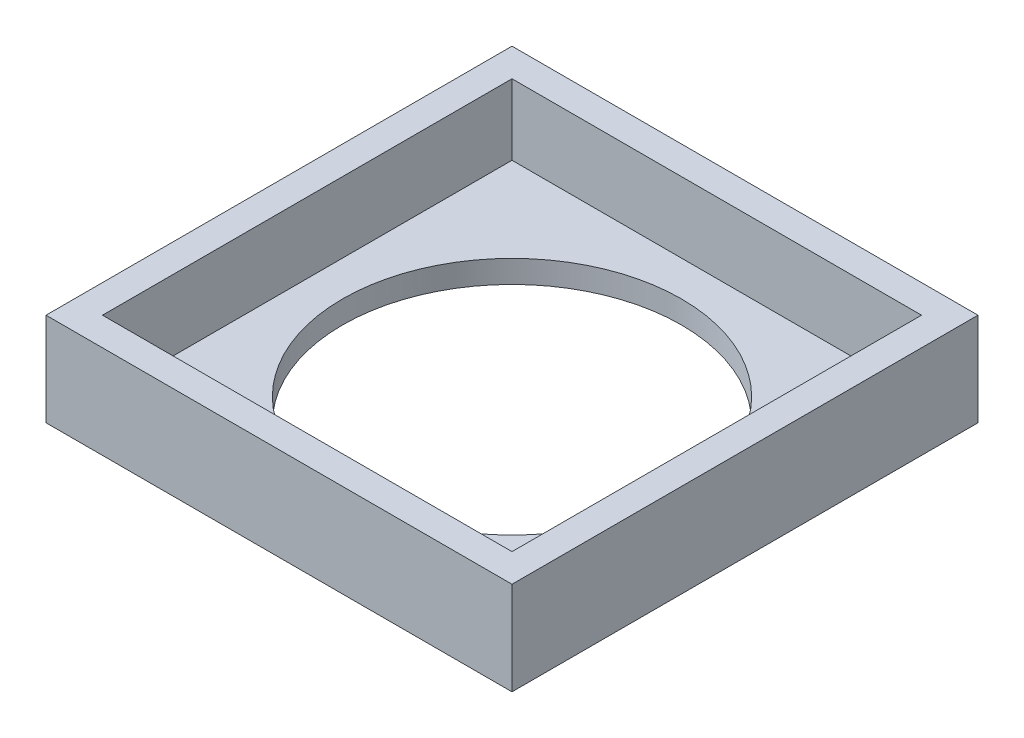
SolidWorks part; units mm, degrees
ref_plane "Alzado" through (0, 0, 0) normal (0, 0, 1) x (1, 0, 0)
ref_plane "Planta" through (0, 0, 0) normal (0, 1, 0) x (1, 0, 0)
ref_plane "Vista lateral" through (0, 0, 0) normal (1, 0, 0) x (0, 0, -1)
sketch "Croquis1" plane through (0, 0, 0) normal (0, 1, 0) x (1, 0, 0)
  line L1 (-16.5, 16.5) -> (16.5, 16.5)
  line L2 (-16.5, 16.5) -> (-16.5, -16.5)
  line L3 (-16.5, -16.5) -> (16.5, -16.5)
  line L4 (16.5, 16.5) -> (16.5, -16.5)
  line L5 (-16.5, 16.5) -> (16.5, -16.5) construction
  line L6 (-16.5, -16.5) -> (16.5, 16.5) construction
  point P0 (0, 0)
  dimension "D1" = 33
  dimension "D2" = 33
extrude "Saliente-Extruir1" add sketch "Croquis1" along normal blind 6.6
sketch "Croquis2" plane through (0, 6.6, 0) normal (0, 1, 0) x (1, 0, 0)
  line L0 (14.5, 14.5) -> (-14.5, 14.5)
  line L1 (-14.5, 14.5) -> (-14.5, -14.5)
  line L2 (-14.5, -14.5) -> (14.5, -14.5)
  line L3 (14.5, -14.5) -> (14.5, 14.5)
  line L4 (16.5, -16.5) -> (16.5, 16.5)
  line L5 (16.5, 16.5) -> (-16.5, 16.5)
  line L6 (-16.5, 16.5) -> (-16.5, -16.5)
  line L7 (-16.5, -16.5) -> (16.5, -16.5)
  line L8 (16.5, -16.5) -> (16.5, 16.5)
  line L9 (16.5, 16.5) -> (-16.5, 16.5)
  line L10 (-16.5, 16.5) -> (-16.5, -16.5)
  line L11 (-16.5, -16.5) -> (16.5, -16.5)
  dimension "D1" = 0
  dimension "D2" = 2
extrude "Cortar-Extruir1" cut sketch "Croquis2" against normal blind 5 contours L2 L3 L0 L1
sketch "Croquis3" plane through (0, 1.6, 0) normal (0, 1, 0) x (1, 0, 0)
  circle A0 centre (0, 0) radius 12
  dimension "D1" = 24
extrude "Cortar-Extruir2" cut sketch "Croquis3" against normal blind 5
